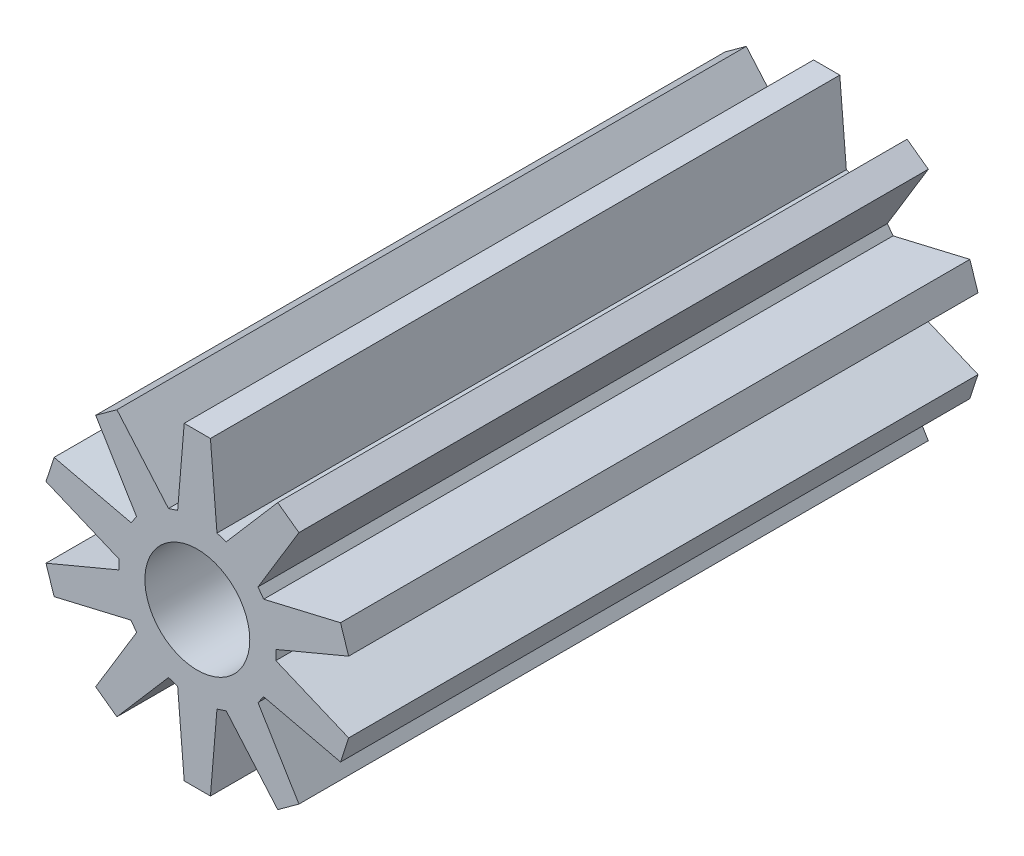
SolidWorks part; units mm, degrees
ref_plane "Front Plane" through (0, 0, 0) normal (0, 0, 1) x (1, 0, 0)
ref_plane "Top Plane" through (0, 0, 0) normal (0, 1, 0) x (1, 0, 0)
ref_plane "Right Plane" through (0, 0, 0) normal (1, 0, 0) x (0, 0, -1)
sketch "Sketch2" plane through (0, 0, 0) normal (0, 0, 1) x (1, 0, 0)
  line L0 (0, 2.4825) -> (0, -3.4036) construction
  line L1 (-0.25, 2.9524) -> (0.25, 2.9524)
  line L2 (-0.25, 2.9524) -> (-0.375, 1.4524)
  line L3 (0.25, 2.9524) -> (0.375, 1.4524)
  line L4 (1.5331, 2.5355) -> (0.5503, 1.3954)
  line L5 (1.5331, 2.5355) -> (1.9376, 2.2416)
  line L6 (1.9376, 2.2416) -> (1.1571, 0.9546)
  line L7 (2.7306, 1.1501) -> (1.2654, 0.8055)
  line L8 (2.7306, 1.1501) -> (2.8851, 0.6746)
  line L9 (2.8851, 0.6746) -> (1.4972, 0.0922)
  line L10 (2.8851, -0.6746) -> (1.4972, -0.0922)
  line L11 (2.8851, -0.6746) -> (2.7306, -1.1501)
  line L12 (2.7306, -1.1501) -> (1.2654, -0.8055)
  line L13 (1.9376, -2.2416) -> (1.1571, -0.9546)
  line L14 (1.9376, -2.2416) -> (1.5331, -2.5355)
  line L15 (1.5331, -2.5355) -> (0.5503, -1.3954)
  line L16 (0.25, -2.9524) -> (0.375, -1.4524)
  line L17 (0.25, -2.9524) -> (-0.25, -2.9524)
  line L18 (-0.25, -2.9524) -> (-0.375, -1.4524)
  line L19 (-1.5331, -2.5355) -> (-0.5503, -1.3954)
  line L20 (-1.5331, -2.5355) -> (-1.9376, -2.2416)
  line L21 (-1.9376, -2.2416) -> (-1.1571, -0.9546)
  line L22 (-2.7306, -1.1501) -> (-1.2654, -0.8055)
  line L23 (-2.7306, -1.1501) -> (-2.8851, -0.6746)
  line L24 (-2.8851, -0.6746) -> (-1.4972, -0.0922)
  line L25 (-2.8851, 0.6746) -> (-1.4972, 0.0922)
  line L26 (-2.8851, 0.6746) -> (-2.7306, 1.1501)
  line L27 (-2.7306, 1.1501) -> (-1.2654, 0.8055)
  line L28 (-1.9376, 2.2416) -> (-1.1571, 0.9546)
  line L29 (-1.9376, 2.2416) -> (-1.5331, 2.5355)
  line L30 (-1.5331, 2.5355) -> (-0.5503, 1.3954)
  line L31 (-0.5503, 1.3954) -> (-0.375, 1.4524)
  line L32 (0.375, 1.4524) -> (0.5503, 1.3954)
  line L33 (1.1571, 0.9546) -> (1.2654, 0.8055)
  line L34 (1.4972, 0.0922) -> (1.4972, -0.0922)
  line L35 (1.2654, -0.8055) -> (1.1571, -0.9546)
  line L36 (0.5503, -1.3954) -> (0.375, -1.4524)
  line L37 (-0.375, -1.4524) -> (-0.5503, -1.3954)
  line L38 (-1.1571, -0.9546) -> (-1.2654, -0.8055)
  line L39 (-1.4972, -0.0922) -> (-1.4972, 0.0922)
  line L40 (-1.2654, 0.8055) -> (-1.1571, 0.9546)
  circle A0 centre (0, 0) radius 1
  point P10 (0, 2.9524)
  point P13 (0, 2.1231)
  point P51 (0, 0)
  point P70 (0, 0)
  dimension "D1" = 2
  dimension "D3" = 1.5
  dimension "D4" = 0.5
  dimension "D5" = 0.75
  dimension "D6" = 10
  dimension "D7" = 10
extrude "Boss-Extrude1" add sketch "Sketch2" along normal blind 12
